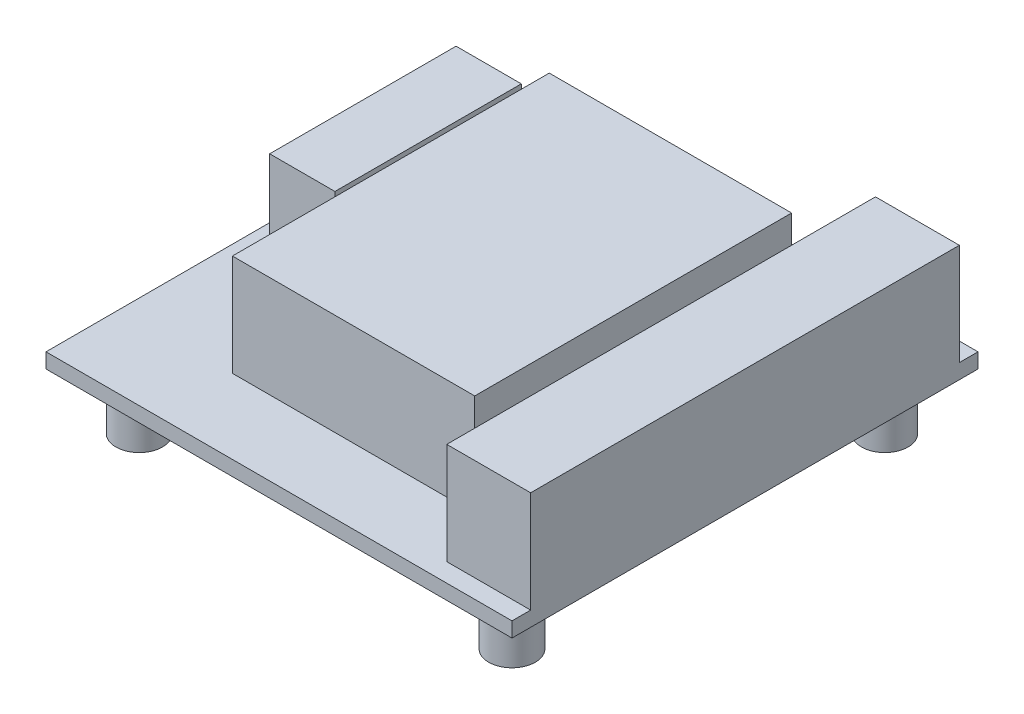
SolidWorks part; units mm, degrees
ref_plane "Front Plane" through (0, 0, 0) normal (0, 0, 1) x (1, 0, 0)
ref_plane "Top Plane" through (0, 0, 0) normal (0, 1, 0) x (1, 0, 0)
ref_plane "Right Plane" through (0, 0, 0) normal (1, 0, 0) x (0, 0, -1)
sketch "SK_P01_Standoff" plane through (0, 0, 0) normal (0, 1, 0) x (1, 0, 0)
  circle A0 centre (-20, 20) radius 2.5
extrude "P01_Standoff" add sketch "SK_P01_Standoff" along normal blind 6
sketch "SK_P02_Standoff" plane through (0, 0, 0) normal (0, 1, 0) x (1, 0, 0)
  circle A0 centre (20, 20) radius 2.5
extrude "P02_Standoff" add sketch "SK_P02_Standoff" along normal blind 6
sketch "SK_P03_Standoff" plane through (0, 0, 0) normal (0, 1, 0) x (1, 0, 0)
  circle A0 centre (-20, -20) radius 2.5
extrude "P03_Standoff" add sketch "SK_P03_Standoff" along normal blind 6
sketch "SK_P04_Standoff" plane through (0, 0, 0) normal (0, 1, 0) x (1, 0, 0)
  circle A0 centre (20, -20) radius 2.5
extrude "P04_Standoff" add sketch "SK_P04_Standoff" along normal blind 6
sketch "SK_P05_DFR0601board50x50" plane through (0, 0, 0) normal (0, 1, 0) x (1, 0, 0)
  line L0 (-25, -25) -> (25, -25)
  line L1 (25, -25) -> (25, 25)
  line L2 (25, 25) -> (-25, 25)
  line L3 (-25, 25) -> (-25, -25)
extrude "P05_DFR0601board50x50" add sketch "SK_P05_DFR0601board50x50" along normal blind 1.6 from offset 6
sketch "SK_P06_MOSFETsandheatsink" plane through (0, 0, 0) normal (0, 1, 0) x (1, 0, 0)
  line L0 (-13, -17) -> (13, -17)
  line L1 (13, -17) -> (13, 17)
  line L2 (13, 17) -> (-13, 17)
  line L3 (-13, 17) -> (-13, -17)
extrude "P06_MOSFETsandheatsink" add sketch "SK_P06_MOSFETsandheatsink" along normal blind 10.9 from offset 7.6
sketch "SK_P07_Powerandmotorterminalswi" plane through (0, 0, 0) normal (0, 1, 0) x (1, 0, 0)
  line L0 (16, -23) -> (25, -23)
  line L1 (25, -23) -> (25, 23)
  line L2 (25, 23) -> (16, 23)
  line L3 (16, 23) -> (16, -23)
extrude "P07_Powerandmotorterminalswi" add sketch "SK_P07_Powerandmotorterminalswi" along normal blind 10.9 from offset 7.6
sketch "SK_P08_Controlheader" plane through (0, 0, 0) normal (0, 1, 0) x (1, 0, 0)
  line L0 (-23, -3) -> (-16, -3)
  line L1 (-16, -3) -> (-16, 17)
  line L2 (-16, 17) -> (-23, 17)
  line L3 (-23, 17) -> (-23, -3)
extrude "P08_Controlheader" add sketch "SK_P08_Controlheader" along normal blind 8.4 from offset 7.6
